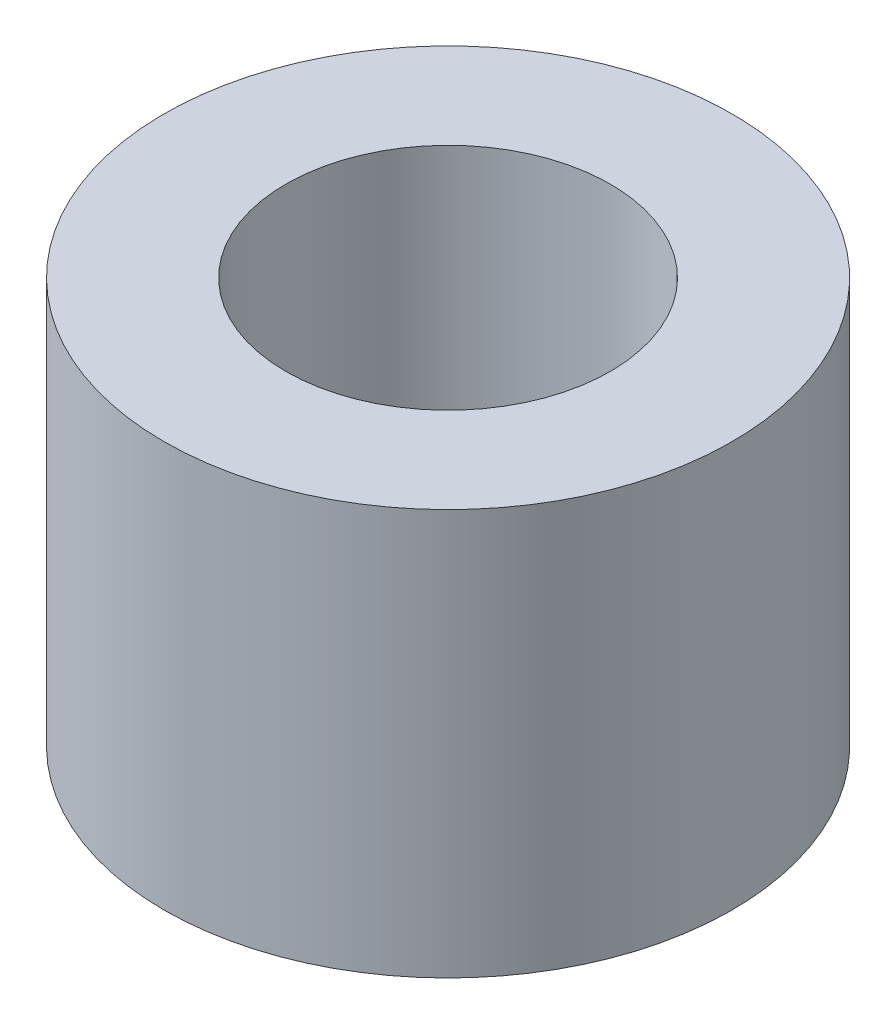
SolidWorks part; units mm, degrees
ref_plane "Front Plane" through (0, 0, 0) normal (0, 0, 1) x (1, 0, 0)
ref_plane "Top Plane" through (0, 0, 0) normal (0, 1, 0) x (1, 0, 0)
ref_plane "Right Plane" through (0, 0, 0) normal (1, 0, 0) x (0, 0, -1)
sketch "Sketch1" plane through (0, 0, 0) normal (0, 1, 0) x (1, 0, 0)
  circle A0 centre (0, 0) radius 3.5
  circle A1 centre (0, 0) radius 2
  dimension "D1" = 7
  dimension "D2" = 4
extrude "Boss-Extrude1" add sketch "Sketch1" along normal blind 5
